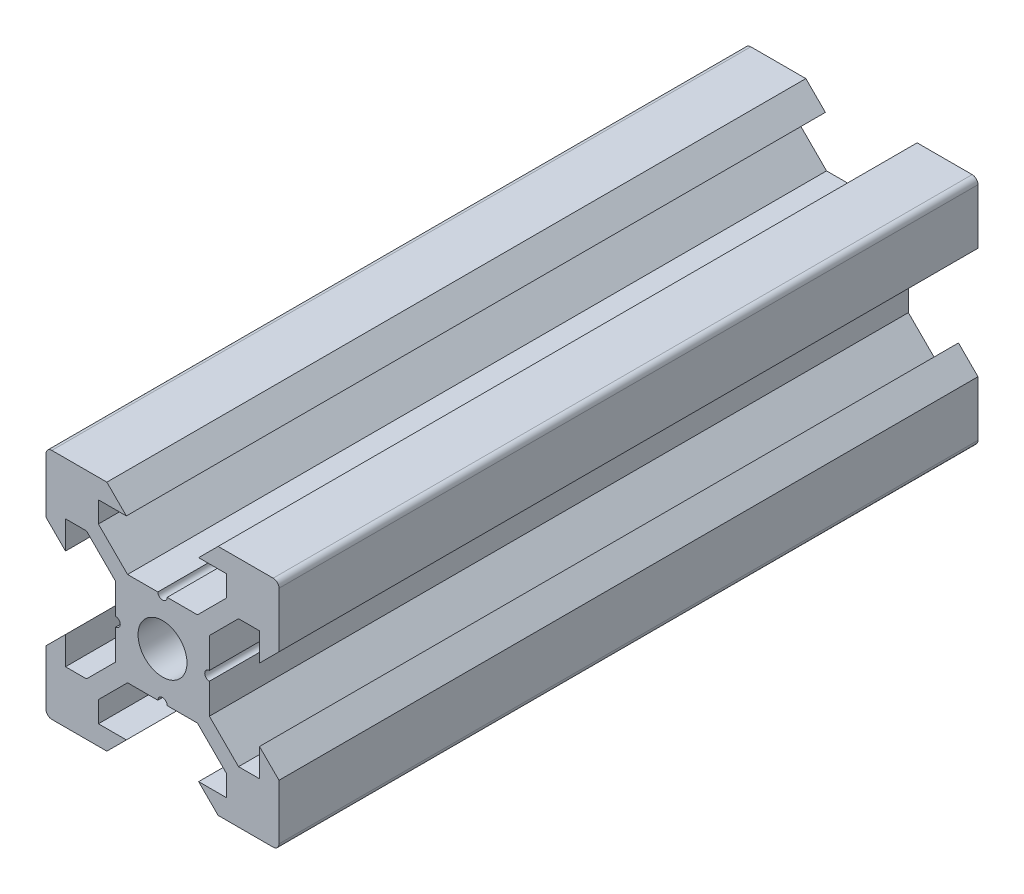
SolidWorks part; units mm, degrees
ref_plane "Front Plane" through (0, 0, 0) normal (0, 0, 1) x (1, 0, 0)
ref_plane "Top Plane" through (0, 0, 0) normal (0, 1, 0) x (1, 0, 0)
ref_plane "Right Plane" through (0, 0, 0) normal (1, 0, 0) x (0, 0, -1)
sketch "Sketch1" plane through (0, 0, 0) normal (0, 0, 1) x (1, 0, 0)
  line L0 (0, 11.7715) -> (0, -11.0375) construction
  line L1 (-10, 10) -> (10, 10) construction
  line L2 (-10, 10) -> (-10, -10) construction
  line L3 (-10, -10) -> (10, -10) construction
  line L4 (10, 10) -> (10, -10) construction
  line L5 (-10, 10) -> (10, -10) construction
  line L6 (-10, -10) -> (10, 10) construction
  line L7 (-5.5, 5.5) -> (5.5, 5.5) construction
  line L8 (-5.5, 5.5) -> (-5.5, -5.5) construction
  line L9 (-5.5, -5.5) -> (5.5, -5.5) construction
  line L10 (5.5, 5.5) -> (5.5, -5.5) construction
  line L11 (-5.5, 5.5) -> (5.5, -5.5) construction
  line L12 (-5.5, -5.5) -> (5.5, 5.5) construction
  line L13 (-10, 10) -> (-4.775, 10)
  line L14 (-4.775, 10) -> (-3.1, 8.325)
  line L15 (-3.1, 8.325) -> (-5.5, 8.325)
  line L16 (-5.5, 8.325) -> (-5.5, 6.525)
  line L17 (-5.5, 6.525) -> (-3, 4.025)
  line L18 (-3, 4.025) -> (3, 4.025)
  line L19 (-2.8044, 0) -> (3.0922, 0) construction
  line L20 (5.5, 6.525) -> (3, 4.025)
  line L21 (5.5, 8.325) -> (5.5, 6.525)
  line L22 (3.1, 8.325) -> (5.5, 8.325)
  line L23 (4.775, 10) -> (3.1, 8.325)
  line L24 (10, 10) -> (4.775, 10)
  line L25 (10, -10) -> (4.775, -10)
  line L26 (4.775, -10) -> (3.1, -8.325)
  line L27 (3.1, -8.325) -> (5.5, -8.325)
  line L28 (5.5, -8.325) -> (5.5, -6.525)
  line L29 (5.5, -6.525) -> (3, -4.025)
  line L30 (-3.1, -8.325) -> (-5.5, -8.325)
  line L31 (-3, -4.025) -> (3, -4.025)
  line L32 (-5.5, -6.525) -> (-3, -4.025)
  line L33 (-5.5, -8.325) -> (-5.5, -6.525)
  line L34 (-4.775, -10) -> (-3.1, -8.325)
  line L35 (-10, -10) -> (-4.775, -10)
  line L36 (-4.025, 3) -> (-4.025, -3)
  line L37 (-6.525, 5.5) -> (-4.025, 3)
  line L38 (-8.325, 5.5) -> (-6.525, 5.5)
  line L39 (-8.325, 3.1) -> (-8.325, 5.5)
  line L40 (-10, 4.775) -> (-8.325, 3.1)
  line L41 (-10, 10) -> (-10, 4.775)
  line L42 (-10, -10) -> (-10, -4.775)
  line L43 (-10, -4.775) -> (-8.325, -3.1)
  line L44 (-8.325, -3.1) -> (-8.325, -5.5)
  line L45 (-8.325, -5.5) -> (-6.525, -5.5)
  line L46 (-6.525, -5.5) -> (-4.025, -3)
  line L47 (10, -10) -> (10, -4.775)
  line L48 (10, -4.775) -> (8.325, -3.1)
  line L49 (8.325, -3.1) -> (8.325, -5.5)
  line L50 (8.325, -5.5) -> (6.525, -5.5)
  line L51 (6.525, -5.5) -> (4.025, -3)
  line L52 (4.025, 3) -> (4.025, -3)
  line L53 (6.525, 5.5) -> (4.025, 3)
  line L54 (8.325, 5.5) -> (6.525, 5.5)
  line L55 (8.325, 3.1) -> (8.325, 5.5)
  line L56 (10, 4.775) -> (8.325, 3.1)
  line L57 (10, 10) -> (10, 4.775)
  circle A0 centre (0, 0) radius 2.1
  point P0 (0, 0)
  point P6 (0, 0)
  point P23 (0, 4.025)
  dimension "D3" = 4.2
  dimension "D1" = 20
  dimension "D2" = 20
  dimension "D4" = 45
  dimension "D5" = 45
  dimension "D6" = 9.55
  dimension "D7" = 6.2
  dimension "D8" = 11
  dimension "D9" = 1.675
  dimension "D10" = 4.3
  dimension "D11" = 9.55
  dimension "D12" = 6.2
  dimension "D13" = 1.675
  dimension "D14" = 4.3
  dimension "D15" = 1.8
  dimension "D16" = 1.8
  dimension "D17" = 45
extrude "Boss-Extrude1" add sketch "Sketch1" along normal blind 60
fillet "Fillet1" radius 0.5 4 edges at (-10, -10, 30) (10, -10, 30) (10, 10, 30) (-10, 10, 30)
sketch "Sketch2" plane through (0, 0, 60) normal (0, 0, 1) x (1, 0, 0)
  line L0 (-0.8203, 0) -> (1.3478, 0) construction
  line L1 (0, 1.2196) -> (0, -1.1398) construction
  line L44 (-10, -4.775) -> (-10, -9.5)
  line L45 (-9.5, -10) -> (-4.775, -10)
  line L46 (-4.775, -10) -> (-3.1, -8.325)
  line L47 (-3.1, -8.325) -> (-5.5, -8.325)
  line L48 (-5.5, -8.325) -> (-5.5, -6.525)
  line L49 (-5.5, -6.525) -> (-3, -4.025)
  line L50 (-3, -4.025) -> (3, -4.025)
  line L51 (3, -4.025) -> (5.5, -6.525)
  line L52 (5.5, -6.525) -> (5.5, -8.325)
  line L53 (5.5, -8.325) -> (3.1, -8.325)
  line L54 (3.1, -8.325) -> (4.775, -10)
  line L55 (4.775, -10) -> (9.5, -10)
  line L56 (10, -9.5) -> (10, -4.775)
  line L57 (10, -4.775) -> (8.325, -3.1)
  line L58 (8.325, -3.1) -> (8.325, -5.5)
  line L59 (8.325, -5.5) -> (6.525, -5.5)
  line L60 (6.525, -5.5) -> (4.025, -3)
  line L61 (4.025, -3) -> (4.025, 3)
  line L62 (4.025, 3) -> (6.525, 5.5)
  line L63 (6.525, 5.5) -> (8.325, 5.5)
  line L64 (8.325, 5.5) -> (8.325, 3.1)
  line L65 (8.325, 3.1) -> (10, 4.775)
  line L66 (10, 4.775) -> (10, 9.5)
  line L67 (9.5, 10) -> (4.775, 10)
  line L68 (4.775, 10) -> (3.1, 8.325)
  line L69 (3.1, 8.325) -> (5.5, 8.325)
  line L70 (5.5, 8.325) -> (5.5, 6.525)
  line L71 (5.5, 6.525) -> (3, 4.025)
  line L72 (3, 4.025) -> (-3, 4.025)
  line L73 (-3, 4.025) -> (-5.5, 6.525)
  line L74 (-5.5, 6.525) -> (-5.5, 8.325)
  line L75 (-5.5, 8.325) -> (-3.1, 8.325)
  line L76 (-3.1, 8.325) -> (-4.775, 10)
  line L77 (-4.775, 10) -> (-9.5, 10)
  line L78 (-10, 9.5) -> (-10, 4.775)
  line L79 (-10, 4.775) -> (-8.325, 3.1)
  line L80 (-8.325, 3.1) -> (-8.325, 5.5)
  line L81 (-8.325, 5.5) -> (-6.525, 5.5)
  line L82 (-6.525, 5.5) -> (-4.025, 3)
  line L83 (-4.025, 3) -> (-4.025, -3)
  line L84 (-4.025, -3) -> (-6.525, -5.5)
  line L85 (-6.525, -5.5) -> (-8.325, -5.5)
  line L86 (-8.325, -5.5) -> (-8.325, -3.1)
  line L87 (-8.325, -3.1) -> (-10, -4.775)
  line L88 (-10, -4.775) -> (-10, -9.5)
  line L89 (-9.5, -10) -> (-4.775, -10)
  line L90 (-4.775, -10) -> (-3.1, -8.325)
  line L91 (-3.1, -8.325) -> (-5.5, -8.325)
  line L92 (-5.5, -8.325) -> (-5.5, -6.525)
  line L93 (-5.5, -6.525) -> (-3, -4.025)
  line L94 (-3, -4.025) -> (3, -4.025)
  line L95 (3, -4.025) -> (5.5, -6.525)
  line L96 (5.5, -6.525) -> (5.5, -8.325)
  line L97 (5.5, -8.325) -> (3.1, -8.325)
  line L98 (3.1, -8.325) -> (4.775, -10)
  line L99 (4.775, -10) -> (9.5, -10)
  line L100 (10, -9.5) -> (10, -4.775)
  line L101 (10, -4.775) -> (8.325, -3.1)
  line L102 (8.325, -3.1) -> (8.325, -5.5)
  line L103 (8.325, -5.5) -> (6.525, -5.5)
  line L104 (6.525, -5.5) -> (4.025, -3)
  line L105 (4.025, -3) -> (4.025, 3)
  line L106 (4.025, 3) -> (6.525, 5.5)
  line L107 (6.525, 5.5) -> (8.325, 5.5)
  line L108 (8.325, 5.5) -> (8.325, 3.1)
  line L109 (8.325, 3.1) -> (10, 4.775)
  line L110 (10, 4.775) -> (10, 9.5)
  line L111 (9.5, 10) -> (4.775, 10)
  line L112 (4.775, 10) -> (3.1, 8.325)
  line L113 (3.1, 8.325) -> (5.5, 8.325)
  line L114 (5.5, 8.325) -> (5.5, 6.525)
  line L115 (5.5, 6.525) -> (3, 4.025)
  line L116 (3, 4.025) -> (-3, 4.025)
  line L117 (-3, 4.025) -> (-5.5, 6.525)
  line L118 (-5.5, 6.525) -> (-5.5, 8.325)
  line L119 (-5.5, 8.325) -> (-3.1, 8.325)
  line L120 (-3.1, 8.325) -> (-4.775, 10)
  line L121 (-4.775, 10) -> (-9.5, 10)
  line L122 (-10, 9.5) -> (-10, 4.775)
  line L123 (-10, 4.775) -> (-8.325, 3.1)
  line L124 (-8.325, 3.1) -> (-8.325, 5.5)
  line L125 (-8.325, 5.5) -> (-6.525, 5.5)
  line L126 (-6.525, 5.5) -> (-4.025, 3)
  line L127 (-4.025, 3) -> (-4.025, -3)
  line L128 (-4.025, -3) -> (-6.525, -5.5)
  line L129 (-6.525, -5.5) -> (-8.325, -5.5)
  line L130 (-8.325, -5.5) -> (-8.325, -3.1)
  line L131 (-8.325, -3.1) -> (-10, -4.775)
  circle A0 centre (-4.025, 0) radius 0.4
  circle A1 centre (4.025, 0) radius 0.4
  circle A2 centre (0, 4.025) radius 0.4
  circle A3 centre (0, -4.025) radius 0.4
  arc A4 (-10, -9.5) -> (-9.5, -10) centre (-9.5, -9.5) ccw
  arc A5 (9.5, -10) -> (10, -9.5) centre (9.5, -9.5) ccw
  arc A6 (10, 9.5) -> (9.5, 10) centre (9.5, 9.5) ccw
  arc A7 (-9.5, 10) -> (-10, 9.5) centre (-9.5, 9.5) ccw
  arc A8 (-10, -9.5) -> (-9.5, -10) centre (-9.5, -9.5) ccw
  arc A9 (9.5, -10) -> (10, -9.5) centre (9.5, -9.5) ccw
  arc A10 (10, 9.5) -> (9.5, 10) centre (9.5, 9.5) ccw
  arc A11 (-9.5, 10) -> (-10, 9.5) centre (-9.5, 9.5) ccw
  dimension "D2" = 0.8
  dimension "D3" = 0.8
  dimension "D1" = 0
extrude "Cut-Extrude1" cut sketch "Sketch2" against normal through all contours L127 A0 | L116 A2 | A1 L105 | A3 L94
